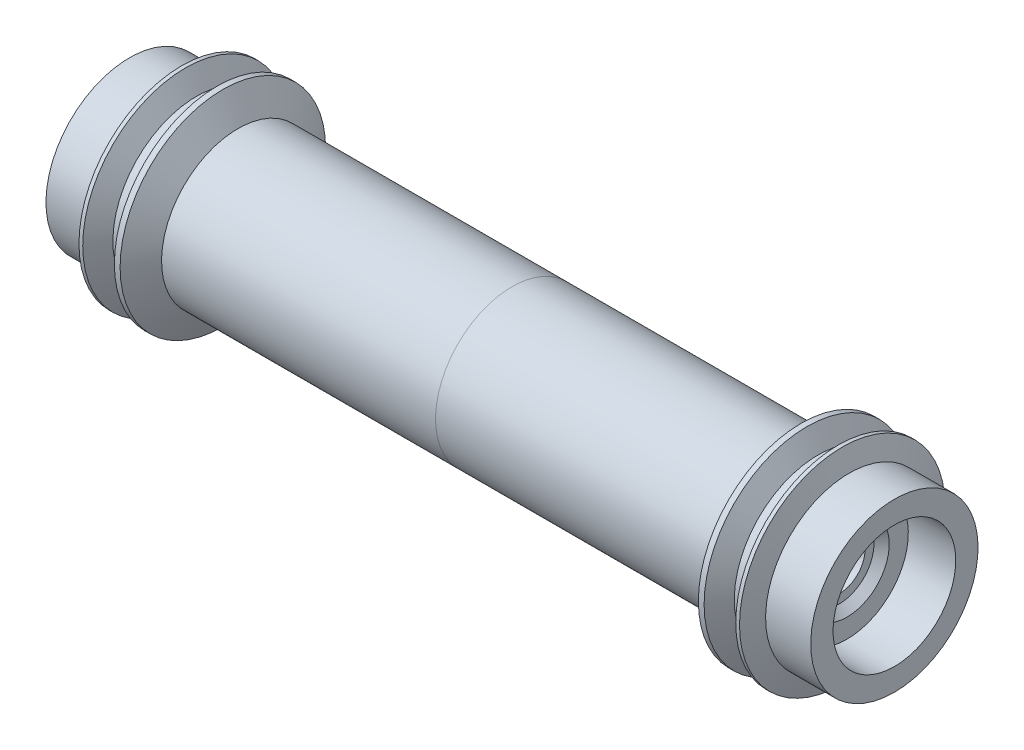
SolidWorks part; units mm, degrees
ref_plane "Front Plane" through (0, 0, 0) normal (0, 0, 1) x (1, 0, 0)
ref_plane "Top Plane" through (0, 0, 0) normal (0, 1, 0) x (1, 0, 0)
ref_plane "Right Plane" through (0, 0, 0) normal (1, 0, 0) x (0, 0, -1)
sketch "Sketch2" plane through (0, 0, 0) normal (0, 0, 1) x (1, 0, 0)
  line L0 (0, 0) -> (0, 28.4375) construction
  line L1 (-25.4, 4.075) -> (-22.25, 4.075) construction
  line L2 (-25.4, 4.075) -> (-25.4, -4.075) construction
  line L3 (-25.4, -4.075) -> (-22.25, -4.075) construction
  line L4 (-22.25, 4.075) -> (-22.25, -4.075) construction
  line L5 (-25.4, 4.075) -> (-22.25, -4.075) construction
  line L6 (-25.4, -4.075) -> (-22.25, 4.075) construction
  line L7 (22.25, 4.5) -> (41.3332, 4.5) construction
  line L8 (22.25, 4.5) -> (22.25, -4.5) construction
  line L9 (22.25, -4.5) -> (41.3332, -4.5) construction
  line L10 (41.3332, 4.5) -> (41.3332, -4.5) construction
  line L11 (22.25, 4.5) -> (41.3332, -4.5) construction
  line L12 (22.25, -4.5) -> (41.3332, 4.5) construction
  line L13 (-25.4, 0) -> (41.3332, 0) construction
  line L14 (-25.4, 5.5562) -> (-22.4, 5.5562)
  line L15 (-22.4, 5.5562) -> (-21.9378, 6.8262)
  line L16 (-21.9378, 6.8262) -> (-21.6882, 6.8262)
  line L19 (-19.5868, 6.8262) -> (-19.2058, 6.8262)
  line L20 (-19.2058, 6.8262) -> (-18.1976, 5.08)
  line L21 (-18.1976, 5.08) -> (0, 5.08)
  line L22 (-25.4, 5.5562) -> (-25.4, 4.075)
  line L23 (-25.4, 4.075) -> (-22.25, 4.075)
  line L24 (-22.25, 4.075) -> (-22.25, 0)
  line L25 (-22.25, 0) -> (0, 0)
  line L26 (0, 0) -> (0, 5.08)
  line L27 (-33.5594, -5.5562) -> (-33.5594, 5.5562) construction
  line L28 (-20.6375, 5.5562) -> (-20.6375, 7.68) construction
  line L29 (-20.6375, 5.5562) -> (20.6375, 5.5562) construction
  line L30 (-25.4, 5.5562) -> (25.4, 5.5562) construction
  line L31 (0, 1.6) -> (-12.5, 1.6)
  line L32 (-12.5, 1.6) -> (-14.1, 0)
  line L33 (-12.5, 1.6) -> (-12.5, -1.6) construction
  line L34 (-12.5, 1.6) -> (12.5, 1.6) construction
  line L35 (-22.25, 1.7145) -> (-15.575, 1.7145)
  line L36 (-15.575, 1.7145) -> (-15.575, 0)
  line L37 (-22.25, 2.805) -> (-21.742, 2.297)
  line L38 (-15.575, 1.7145) -> (-28.575, 1.7145) construction
  line L39 (-15.575, 1.7145) -> (-15.575, -1.7145) construction
  line L40 (-15.575, -1.7145) -> (-28.575, -1.7145) construction
  line L41 (-28.575, 1.7145) -> (-28.575, -1.7145) construction
  line L42 (-21.742, 2.297) -> (-21.742, 0)
  line L43 (-20.955, 5.5562) -> (-20.32, 5.5562)
  line L44 (-20.32, 5.5562) -> (-19.5868, 6.8262)
  line L45 (-21.6882, 6.8262) -> (-20.955, 5.5562)
  point P0 (-23.825, 0)
  point P5 (31.7916, 0)
  point P27 (-33.5594, 0)
  point P28 (-19.3963, 6.8262)
  point P29 (-12.5, 0)
  point P33 (0, 5.5562)
  point P36 (0, 1.6)
  point P48 (-15.575, 0)
  point P51 (0, 5.5562)
  point P54 (-20.6375, 5.5562)
  dimension "D1" = 3.15
  dimension "D3" = 5.08
  dimension "D4" = 11.1125
  dimension "D5" = 8.15
  dimension "D6" = 60
  dimension "D7" = 60
  dimension "D8" = 1.27
  dimension "D9" = 70
  dimension "D10" = 41.275
  dimension "D11" = 50.8
  dimension "D12" = 0.381
  dimension "D13" = 45
  dimension "D14" = 25
  dimension "D15" = 3.2
  dimension "D16" = 3.429
  dimension "D17" = 3.175
  dimension "D18" = 1.27
  dimension "D19" = 0.508
  dimension "D20" = 45
  dimension "D21" = 13
  dimension "D22" = 3
  dimension "D23" = 0.635
revolve "Revolve1" add sketch "Sketch2" angle 360 about L13
mirror "Mirror1" about plane through (0, 0, 0) normal (1, 0, 0) of bodies 101
chamfer "Chamfer1" distance 0.508 angle 45 1 edges at (-25.4, -4.075, 0)
